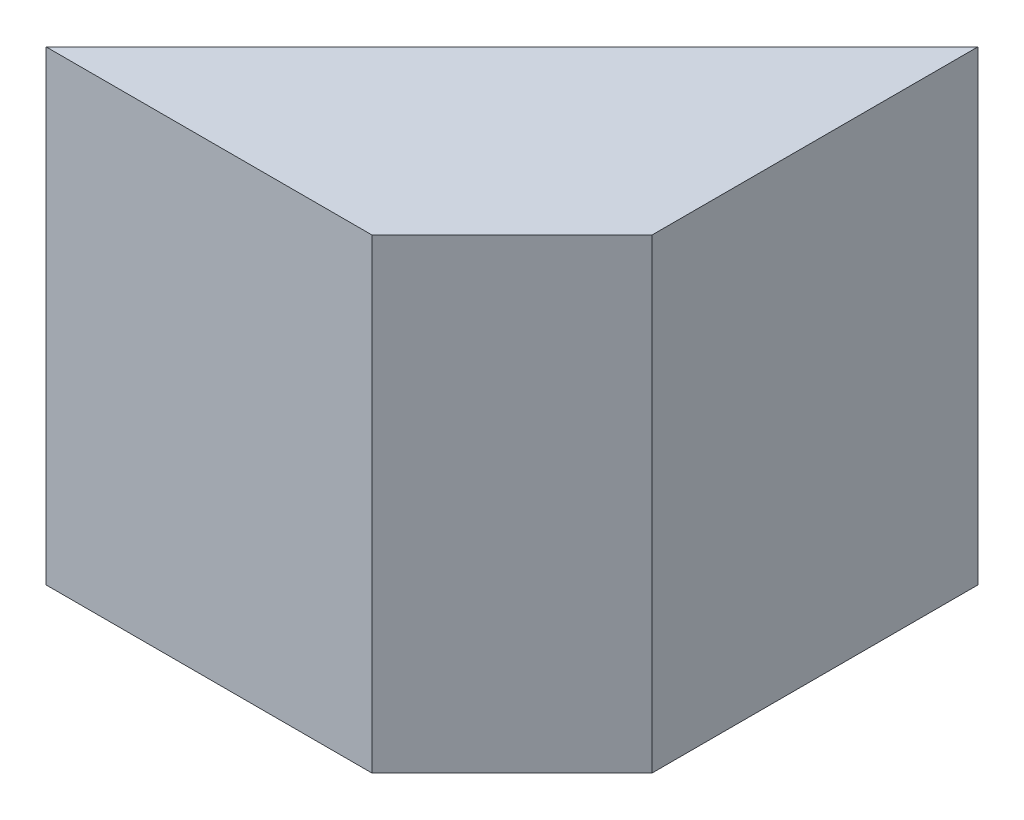
SolidWorks part; units mm, degrees
ref_plane "Front Plane" through (0, 0, 0) normal (0, 0, 1) x (1, 0, 0)
ref_plane "Top Plane" through (0, 0, 0) normal (0, 1, 0) x (1, 0, 0)
ref_plane "Right Plane" through (0, 0, 0) normal (1, 0, 0) x (0, 0, -1)
sketch "Sketch1" plane through (0, 0, 0) normal (0, 1, 0) x (1, 0, 0)
  line L0 (0, 0) -> (10, 10)
  line L1 (10, 10) -> (10, 0)
  line L2 (10, 0) -> (0, 0)
  dimension "D1" = 10
extrude "Boss-Extrude1" add sketch "Sketch1" along normal blind 10
chamfer "Chamfer2" distance 3 angle 45 1 edges at (10, 5, 0)
